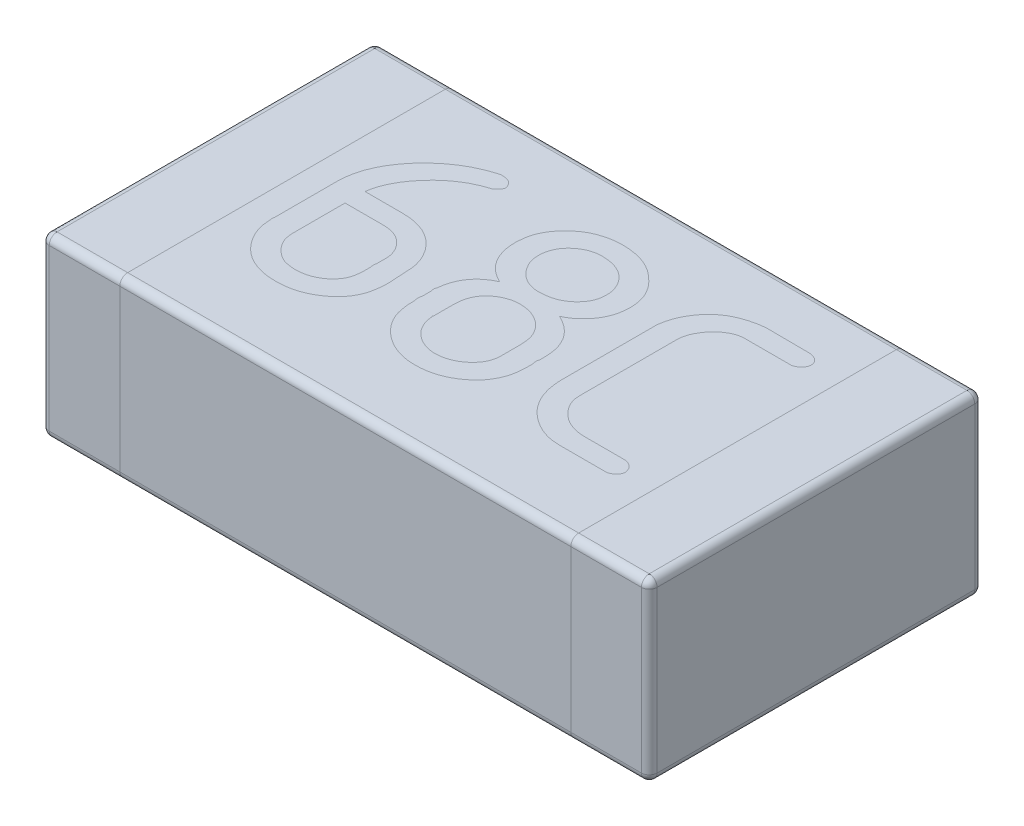
SolidWorks part; units mm, degrees
ref_plane "Front Plane" through (0, 0, 0) normal (0, 0, 1) x (1, 0, 0)
ref_plane "Top Plane" through (0, 0, 0) normal (0, 1, 0) x (1, 0, 0)
ref_plane "Right Plane" through (0, 0, 0) normal (1, 0, 0) x (0, 0, -1)
sketch "Sketch1" plane through (0, 0, 0) normal (0, 1, 0) x (1, 0, 0)
  line L1 (-0.755, -0.425) -> (0.755, -0.425)
  line L2 (-0.775, -0.405) -> (-0.775, 0.405)
  line L3 (-0.755, 0.425) -> (0.755, 0.425)
  line L4 (0.775, -0.405) -> (0.775, 0.405)
  line L5 (-0.775, -0.425) -> (0.775, 0.425) construction
  line L6 (-0.775, 0.425) -> (0.775, -0.425) construction
  arc A4 (-0.775, -0.405) -> (-0.755, -0.425) centre (-0.755, -0.405) ccw
  arc A5 (0.755, -0.425) -> (0.775, -0.405) centre (0.755, -0.405) ccw
  arc A6 (0.775, 0.405) -> (0.755, 0.425) centre (0.755, 0.405) ccw
  arc A7 (-0.755, 0.425) -> (-0.775, 0.405) centre (-0.755, 0.405) ccw
  point P0 (0, 0)
  dimension "D4" = 0.02
  dimension "D1" = 1.55
  dimension "D2" = 0.85
extrude "Boss-Extrude1" add sketch "Sketch1" along normal mid plane 0.45
sketch "Sketch3" plane through (0, 0.225, 0) normal (0, 1, 0) x (1, 0, 0)
  line L0 (-0.575, 0) -> (0.575, 0) construction
  line L1 (-0.575, -0.5133) -> (-0.575, 0.5133)
  line L2 (0.575, -0.5133) -> (0.575, 0.5133)
  line L3 (0, -0.25) -> (0, 0.25) construction
  line L6 (-0.575, -0.25) -> (0.575, -0.25) construction
  text T0 "<b>68C</b>" font "SWIsop1" height 0.53
  point P4 (0, 0)
  point P8 (-0.575, 0)
  point P11 (0.575, 0)
  point P14 (0, 0)
  point P17 (0, -0.25)
  dimension "D1" = 1.15
  dimension "D2" = 0.5
sketch "Sketch4" plane through (0, 0, 0.425) normal (0, 0, 1) x (1, 0, 0)
  line L0 (-0.575, 0.225) -> (-0.575, -0.5946)
  line L1 (0.575, 0.225) -> (0.575, -0.5946)
sketch "Sketch5" plane through (0, 0, -0.425) normal (0, 0, -1) x (-1, 0, 0)
  line L0 (-0.575, 0.225) -> (-0.575, -0.5946) construction
  line L1 (-0.575, 0.225) -> (-0.575, -0.5946)
  line L2 (0.575, 0.225) -> (0.575, -0.5946) construction
  line L3 (0.575, 0.225) -> (0.575, -0.5946)
sketch "Sketch6" plane through (0, -0.225, 0) normal (0, -1, 0) x (1, 0, 0)
  line L0 (0.575, 0.5133) -> (0.575, -0.5133) construction
  line L1 (-0.575, 0.5133) -> (-0.575, -0.5133) construction
  line L2 (0.575, 0.5133) -> (0.575, -0.5133)
  line L3 (-0.575, 0.5133) -> (-0.575, -0.5133)
split line "Split Line2"
split line "Split Line3"
split line "Split Line4"
split line "Split Line5"
fillet "Fillet2" radius 0.02 24 edges at (-0.665, -0.225, 0.425) (0, -0.225, 0.425) (0.665, -0.225, 0.425) (-0.7691, -0.225, 0.4191) (-0.775, -0.225, 0) (-0.7691, -0.225, -0.4191) (-0.665, -0.225, -0.425) (0.665, -0.225, -0.425) (0, -0.225, -0.425) (0.7691, -0.225, -0.4191) (0.775, -0.225, 0) (0.7691, -0.225, 0.4191) (-0.7691, 0.225, 0.4191) (-0.775, 0.225, 0) (-0.7691, 0.225, -0.4191) (-0.665, 0.225, -0.425) (0.665, 0.225, -0.425) (0, 0.225, -0.425) (0.7691, 0.225, -0.4191) (0.775, 0.225, 0) (0.7691, 0.225, 0.4191) (-0.665, 0.225, 0.425) (0, 0.225, 0.425) (0.665, 0.225, 0.425)
